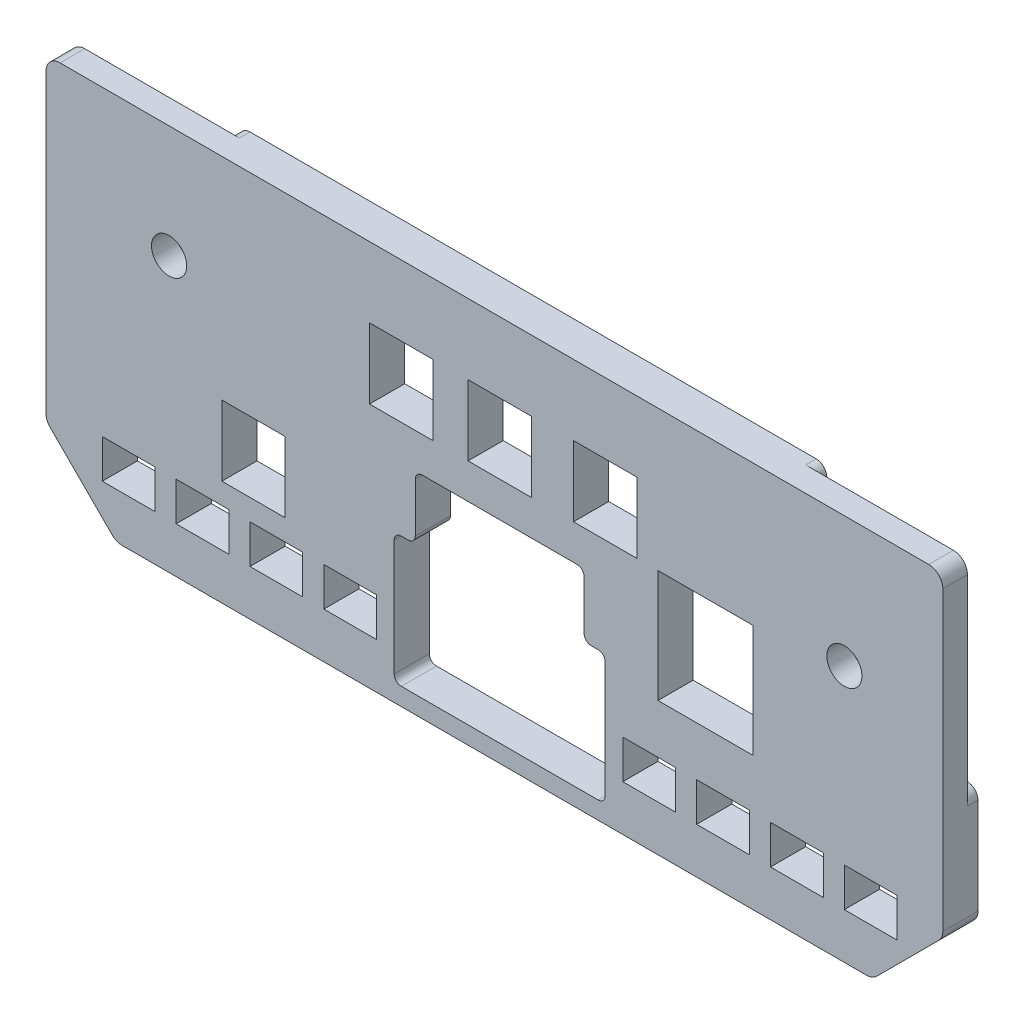
SolidWorks part; units mm, degrees
ref_plane "Front Plane" through (0, 0, 0) normal (0, 0, 1) x (1, 0, 0)
ref_plane "Top Plane" through (0, 0, 0) normal (0, 1, 0) x (1, 0, 0)
ref_plane "Right Plane" through (0, 0, 0) normal (1, 0, 0) x (0, 0, -1)
sketch "Sketch1" plane through (0, 0, 0) normal (0, 0, 1) x (1, 0, 0)
  line L0 (-168.6542, -33.4123) -> (-150.9974, -51.0692)
  line L1 (-165.8258, 57.7593) -> (81.1742, 57.7593)
  line L2 (-169.8258, 53.7593) -> (-169.8258, -30.5839)
  line L3 (-148.1689, -52.2407) -> (63.5174, -52.2407)
  line L4 (85.1742, 53.7593) -> (85.1742, -30.5839)
  line L5 (-77.8258, 37.7593) -> (-59.8258, 37.7593)
  line L6 (-77.8258, 37.7593) -> (-77.8258, 17.7593)
  line L7 (-77.8258, 17.7593) -> (-59.8258, 17.7593)
  line L8 (-59.8258, 37.7593) -> (-59.8258, 17.7593)
  line L9 (-49.8258, 37.7593) -> (-31.8258, 37.7593)
  line L10 (-49.8258, 37.7593) -> (-49.8258, 17.7593)
  line L11 (-49.8258, 17.7593) -> (-31.8258, 17.7593)
  line L12 (-31.8258, 37.7593) -> (-31.8258, 17.7593)
  line L13 (-19.8258, 37.7593) -> (-1.8258, 37.7593)
  line L14 (-19.8258, 37.7593) -> (-19.8258, 17.7593)
  line L15 (-19.8258, 17.7593) -> (-1.8258, 17.7593)
  line L16 (-1.8258, 37.7593) -> (-1.8258, 17.7593)
  line L17 (-119.8258, -2.2407) -> (-101.8258, -2.2407)
  line L18 (-119.8258, -2.2407) -> (-119.8258, -22.2407)
  line L19 (-119.8258, -22.2407) -> (-101.8258, -22.2407)
  line L20 (-101.8258, -2.2407) -> (-101.8258, -22.2407)
  line L21 (4.1742, 17.7593) -> (31.1742, 17.7593)
  line L22 (4.1742, 17.7593) -> (4.1742, -14.2407)
  line L23 (4.1742, -14.2407) -> (31.1742, -14.2407)
  line L24 (31.1742, 17.7593) -> (31.1742, -14.2407)
  line L25 (66.3458, -51.0692) -> (84.0026, -33.4123)
  arc A0 (85.1742, 53.7593) -> (81.1742, 57.7593) centre (81.1742, 53.7593) ccw
  arc A1 (-165.8258, 57.7593) -> (-169.8258, 53.7593) centre (-165.8258, 53.7593) ccw
  arc A2 (-169.8258, -30.5839) -> (-168.6542, -33.4123) centre (-165.8258, -30.5839) ccw
  arc A3 (-150.9974, -51.0692) -> (-148.1689, -52.2407) centre (-148.1689, -48.2407) ccw
  arc A4 (63.5174, -52.2407) -> (66.3458, -51.0692) centre (63.5174, -48.2407) ccw
  arc A5 (85.1742, -30.5839) -> (84.0026, -33.4123) centre (81.1742, -30.5839) cw
  point P1 (85.1742, -52.2407)
  point P2 (-169.8258, -52.2407)
  point P26 (85.1742, 57.7593)
  point P29 (-169.8258, 57.7593)
  point P36 (-169.8258, -32.2407)
  point P39 (-149.8258, -52.2407)
  point P42 (65.1742, -52.2407)
  point P45 (85.1742, -32.2407)
  dimension "D23" = 4
  dimension "D24" = 4
  dimension "D1" = 255
  dimension "D2" = 110
  dimension "D3" = 18
  dimension "D4" = 20
  dimension "D5" = 18
  dimension "D6" = 20
  dimension "D7" = 18
  dimension "D8" = 20
  dimension "D9" = 92
  dimension "D10" = 20
  dimension "D11" = 120
  dimension "D12" = 20
  dimension "D13" = 20
  dimension "D14" = 150
  dimension "D15" = 18
  dimension "D16" = 20
  dimension "D17" = 60
  dimension "D18" = 50
  dimension "D19" = 27
  dimension "D20" = 32
  dimension "D21" = 40
  dimension "D22" = 54
extrude "Boss-Extrude1" add sketch "Sketch1" along normal blind 10
sketch "Sketch2" plane through (0, 0, 10) normal (0, 0, 1) x (1, 0, 0)
  line L0 (-169.8258, 53.7593) -> (-169.8258, -30.5839) construction
  line L1 (-153.8258, -28.2407) -> (-138.8258, -28.2407)
  line L2 (-153.8258, -28.2407) -> (-153.8258, -39.2407)
  line L3 (-153.8258, -39.2407) -> (-138.8258, -39.2407)
  line L4 (-138.8258, -28.2407) -> (-138.8258, -39.2407)
  line L5 (-148.1689, -52.2407) -> (63.5174, -52.2407) construction
  line L6 (-40.8258, 66.6715) -> (-40.8258, -69.3654) construction
  line L7 (-132.8258, -28.2407) -> (-117.8258, -28.2407)
  line L8 (-132.8258, -28.2407) -> (-132.8258, -39.2407)
  line L9 (-132.8258, -39.2407) -> (-117.8258, -39.2407)
  line L10 (-117.8258, -28.2407) -> (-117.8258, -39.2407)
  line L11 (-111.8258, -28.2407) -> (-96.8258, -28.2407)
  line L12 (-111.8258, -28.2407) -> (-111.8258, -39.2407)
  line L13 (-111.8258, -39.2407) -> (-96.8258, -39.2407)
  line L14 (-96.8258, -28.2407) -> (-96.8258, -39.2407)
  line L15 (-90.8258, -28.2407) -> (-75.8258, -28.2407)
  line L16 (-90.8258, -28.2407) -> (-90.8258, -39.2407)
  line L17 (-90.8258, -39.2407) -> (-75.8258, -39.2407)
  line L18 (-75.8258, -28.2407) -> (-75.8258, -39.2407)
  line L19 (-49.8258, 37.7593) -> (-49.8258, 17.7593) construction
  line L20 (-5.8258, -28.2407) -> (-5.8258, -39.2407)
  line L21 (9.1742, -39.2407) -> (-5.8258, -39.2407)
  line L22 (9.1742, -28.2407) -> (9.1742, -39.2407)
  line L23 (9.1742, -28.2407) -> (-5.8258, -28.2407)
  line L24 (15.1742, -28.2407) -> (15.1742, -39.2407)
  line L25 (30.1742, -39.2407) -> (15.1742, -39.2407)
  line L26 (30.1742, -28.2407) -> (30.1742, -39.2407)
  line L27 (30.1742, -28.2407) -> (15.1742, -28.2407)
  line L28 (36.1742, -28.2407) -> (36.1742, -39.2407)
  line L29 (51.1742, -39.2407) -> (36.1742, -39.2407)
  line L30 (51.1742, -28.2407) -> (51.1742, -39.2407)
  line L31 (51.1742, -28.2407) -> (36.1742, -28.2407)
  line L32 (57.1742, -28.2407) -> (57.1742, -39.2407)
  line L33 (72.1742, -39.2407) -> (57.1742, -39.2407)
  line L34 (72.1742, -28.2407) -> (72.1742, -39.2407)
  line L35 (72.1742, -28.2407) -> (57.1742, -28.2407)
  point P20 (-125.3258, -39.2407)
  dimension "D1" = 15
  dimension "D2" = 11
  dimension "D3" = 16
  dimension "D4" = 13
  dimension "D5" = 15
  dimension "D6" = 15
  dimension "D7" = 15
  dimension "D8" = 6
  dimension "D9" = 6
  dimension "D10" = 6
  dimension "D11" = 13
  dimension "D12" = 11
  dimension "D13" = 13
  dimension "D14" = 13
  dimension "D15" = 11
  dimension "D16" = 11
  dimension "D17" = 9
extrude "Cut-Extrude1" cut sketch "Sketch2" against normal blind 10
sketch "Sketch3" plane through (0, 0, 0) normal (0, 0, -1) x (-1, 0, 0)
  line L0 (-81.1742, 57.7593) -> (165.8258, 57.7593) construction
  line L1 (-42.1742, 57.7593) -> (-85.1742, 57.7593)
  line L2 (-42.1742, 57.7593) -> (-42.1742, 7.7593)
  line L3 (-50.1742, -0.2407) -> (-85.1742, -0.2407)
  line L4 (-85.1742, 57.7593) -> (-85.1742, -0.2407)
  line L5 (-85.1742, -30.5839) -> (-85.1742, 53.7593) construction
  line L6 (169.8258, 53.7593) -> (169.8258, -30.5839) construction
  line L7 (124.8258, 57.7593) -> (169.8258, 57.7593)
  line L8 (124.8258, 57.7593) -> (124.8258, -1.2407)
  line L9 (148.8258, -2.2407) -> (169.8258, -2.2407)
  line L10 (169.8258, 57.7593) -> (169.8258, -2.2407)
  line L13 (124.8258, -1.2407) -> (124.8258, -6.2407)
  line L14 (127.8258, -9.2407) -> (145.8258, -9.2407)
  line L15 (148.8258, -2.2407) -> (148.8258, -6.2407)
  arc A0 (-50.1742, -0.2407) -> (-42.1742, 7.7593) centre (-50.1742, 7.7593) ccw
  arc A1 (145.8258, -9.2407) -> (148.8258, -6.2407) centre (145.8258, -6.2407) ccw
  arc A2 (127.8258, -9.2407) -> (124.8258, -6.2407) centre (127.8258, -6.2407) cw
  point P23 (124.8258, -9.2407)
  dimension "D3" = 8
  dimension "D8" = 3
  dimension "D1" = 43
  dimension "D2" = 58
  dimension "D4" = 60
  dimension "D5" = 45
  dimension "D6" = 21
  dimension "D7" = 8
extrude "Cut-Extrude2" cut sketch "Sketch3" against normal blind 3
fillet "Fillet1" radius 3 1 edges at (-148.8258, -2.2407, 1.5)
fillet "Fillet2" radius 3 1 edges at (-169.8258, -2.2407, 1.5)
fillet "Fillet3" radius 3 1 edges at (-124.8258, 57.7593, 1.5)
fillet "Fillet4" radius 3 1 edges at (42.1742, 57.7593, 1.5)
fillet "Fillet5" radius 3 1 edges at (85.1742, -0.2407, 1.5)
sketch "Sketch4" plane through (0, 0, 0) normal (0, 0, -1) x (-1, 0, 0)
  line L1 (68.8258, -47.2407) -> (12.8258, -47.2407)
  line L2 (70.8258, -45.2407) -> (70.8258, -12.2407)
  line L3 (62.8258, 7.7593) -> (18.8258, 7.7593)
  line L4 (10.8258, -45.2407) -> (10.8258, -12.2407)
  line L5 (5.8258, -28.2407) -> (5.8258, -39.2407) construction
  line L6 (-39.1742, 57.7593) -> (121.8258, 57.7593) construction
  line L8 (12.8258, -10.2407) -> (14.8258, -10.2407)
  line L11 (16.8258, -8.2407) -> (16.8258, 5.7593)
  line L14 (68.8258, -10.2407) -> (66.8258, -10.2407)
  line L15 (64.8258, 5.7593) -> (64.8258, -8.2407)
  arc A0 (68.8258, -47.2407) -> (70.8258, -45.2407) centre (68.8258, -45.2407) ccw
  arc A1 (70.8258, -12.2407) -> (68.8258, -10.2407) centre (68.8258, -12.2407) ccw
  arc A2 (66.8258, -10.2407) -> (64.8258, -8.2407) centre (66.8258, -8.2407) cw
  arc A3 (64.8258, 5.7593) -> (62.8258, 7.7593) centre (62.8258, 5.7593) ccw
  arc A4 (18.8258, 7.7593) -> (16.8258, 5.7593) centre (18.8258, 5.7593) ccw
  arc A5 (16.8258, -8.2407) -> (14.8258, -10.2407) centre (14.8258, -8.2407) cw
  arc A6 (12.8258, -10.2407) -> (10.8258, -12.2407) centre (12.8258, -12.2407) ccw
  arc A7 (10.8258, -45.2407) -> (12.8258, -47.2407) centre (12.8258, -45.2407) ccw
  point P16 (70.8258, -10.2407)
  point P19 (64.8258, -10.2407)
  point P22 (64.8258, 7.7593)
  point P25 (16.8258, 7.7593)
  point P28 (16.8258, -10.2407)
  point P31 (10.8258, -10.2407)
  dimension "D1" = 2
  dimension "D3" = 5
  dimension "D4" = 50
  dimension "D5" = 18
  dimension "D6" = 18
  dimension "D7" = 6
  dimension "D8" = 6
extrude "Cut-Extrude3" cut sketch "Sketch4" against normal blind 10
sketch "Sketch5" plane through (0, 0, 3) normal (0, 0, -1) x (-1, 0, 0)
  line L0 (-85.1742, 53.7593) -> (-85.1742, -3.2407) construction
  line L1 (-39.1742, 57.7593) -> (-81.1742, 57.7593) construction
  line L2 (169.8258, -5.2407) -> (169.8258, 53.7593) construction
  line L3 (165.8258, 57.7593) -> (121.8258, 57.7593) construction
  circle A0 centre (-57.1742, 20.7593) radius 5
  circle A1 centre (134.8258, 25.7593) radius 5
  point P10 (0, 0)
  point P12 (139.5447, 25.0367)
  dimension "D2" = 10
  dimension "D6" = 10
  dimension "D1" = 28
  dimension "D3" = 37
  dimension "D4" = 35
  dimension "D5" = 32
extrude "Cut-Extrude4" cut sketch "Sketch5" against normal blind 7
